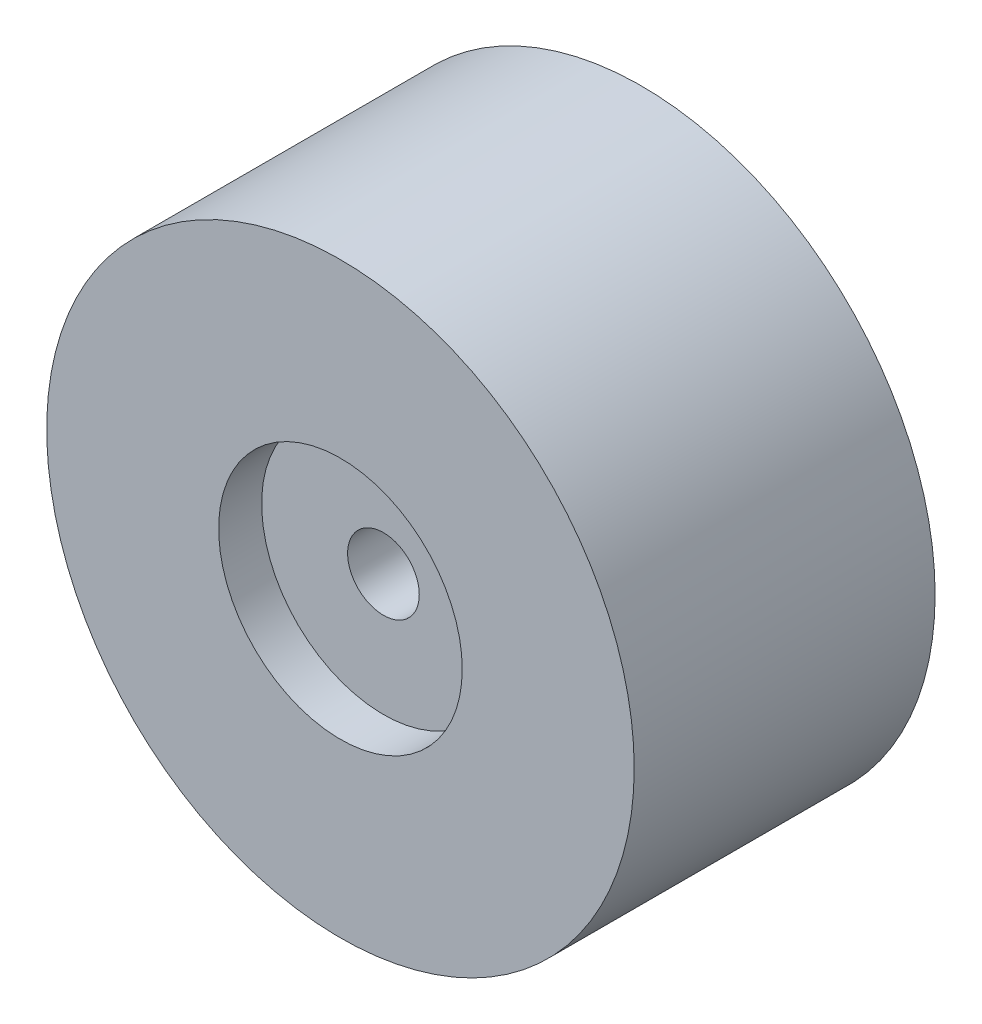
SolidWorks part; units mm, degrees
ref_plane "前基準面" through (0, 0, 0) normal (0, 0, 1) x (1, 0, 0)
ref_plane "上基準面" through (0, 0, 0) normal (0, 1, 0) x (1, 0, 0)
ref_plane "右基準面" through (0, 0, 0) normal (1, 0, 0) x (0, 0, -1)
sketch "草圖1" plane through (0, 0, 0) normal (0, 0, 1) x (1, 0, 0)
  circle A0 centre (0, 0) radius 10.25
  circle A1 centre (0, 0) radius 1.25
  dimension "D1" = 2.5
  dimension "D2" = 20.5
extrude "填料-伸長1" add sketch "草圖1" along normal blind 9
sketch "草圖2" plane through (0, 0, 9) normal (0, 0, 1) x (1, 0, 0)
  circle A0 centre (0, 0) radius 4.25
  circle A1 centre (0, 0) radius 10.25
  dimension "D1" = 8.5
extrude "填料-伸長2" add sketch "草圖2" along normal blind 1.5
